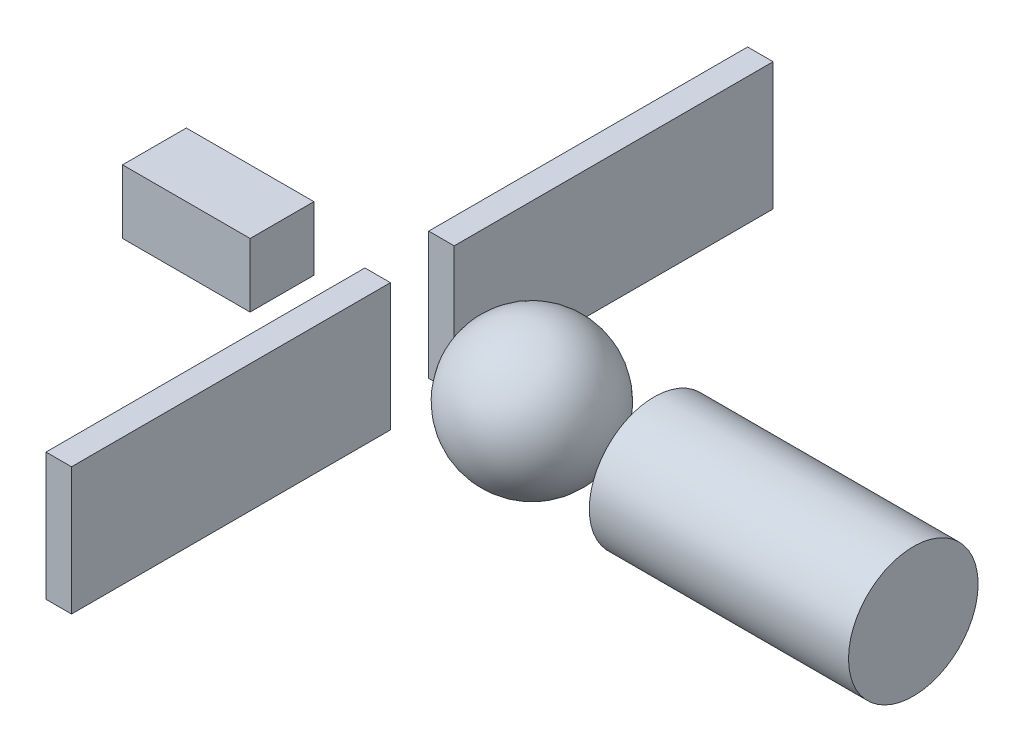
SolidWorks part; units mm, degrees
ref_plane "Front Plane" through (0, 0, 0) normal (0, 0, 1) x (1, 0, 0)
ref_plane "Top Plane" through (0, 0, 0) normal (0, 1, 0) x (1, 0, 0)
ref_plane "Right Plane" through (0, 0, 0) normal (1, 0, 0) x (0, 0, -1)
sketch "Sketch2" plane through (0, 0, 0) normal (0, 0, 1) x (1, 0, 0)
  line L0 (0, 0) -> (50, 0) construction
  line L1 (-200, -25) -> (-100, -25)
  line L2 (-200, -25) -> (-200, 25)
  line L3 (-200, 25) -> (-100, 25)
  line L4 (-100, -25) -> (-100, 25)
  line L5 (-200, -25) -> (-100, 25) construction
  line L6 (-200, 25) -> (-100, -25) construction
  point P0 (-150, 0)
  dimension "D1" = 50
  dimension "D2" = 100
  dimension "D3" = 100
  dimension "D4" = 50
extrude "Boss-Extrude2" add sketch "Sketch2" along normal mid plane 50
sketch "Sketch3" plane through (0, 0, 0) normal (0, 1, 0) x (1, 0, 0)
  line L0 (0, 0) -> (394.9, 0) construction
  line L1 (40, 0) -> (151.7, 0)
  line L3 (191.7, 0) -> (394.9, 0)
  line L4 (191.7, 0) -> (191.7, 50.8)
  line L5 (191.7, 50.8) -> (394.9, 50.8)
  line L6 (394.9, 0) -> (394.9, 50.8)
  arc A0 (40, 0) -> (151.7, 0) centre (95.85, 0) cw
  dimension "D1" = 55.85
  dimension "D2" = 95.85
  dimension "D3" = 50.8
  dimension "D4" = 203.2
  dimension "D5" = 95.85
revolve "Revolve1" add sketch "Sketch3" angle 360 about L0
sketch "Sketch4" plane through (0, 0, 0) normal (0, 1, 0) x (1, 0, 0)
  line L0 (0, 0) -> (91.7941, 0) construction
  line L1 (10, 275) -> (-10, 275)
  line L2 (10, 275) -> (10, 25)
  line L3 (10, 25) -> (-10, 25)
  line L4 (-10, 275) -> (-10, 25)
  line L5 (10, 275) -> (-10, 25) construction
  line L6 (10, 25) -> (-10, 275) construction
  line L7 (10, -25) -> (-10, -275) construction
  line L8 (10, -275) -> (-10, -25) construction
  line L9 (-10, -275) -> (-10, -25)
  line L10 (10, -25) -> (-10, -25)
  line L11 (10, -275) -> (10, -25)
  line L12 (10, -275) -> (-10, -275)
  point P0 (0, 150)
  point P12 (0, -150)
  dimension "D1" = 20
  dimension "D2" = 250
  dimension "D3" = 25
extrude "Boss-Extrude3" add sketch "Sketch4" along normal mid plane 100 separate body
